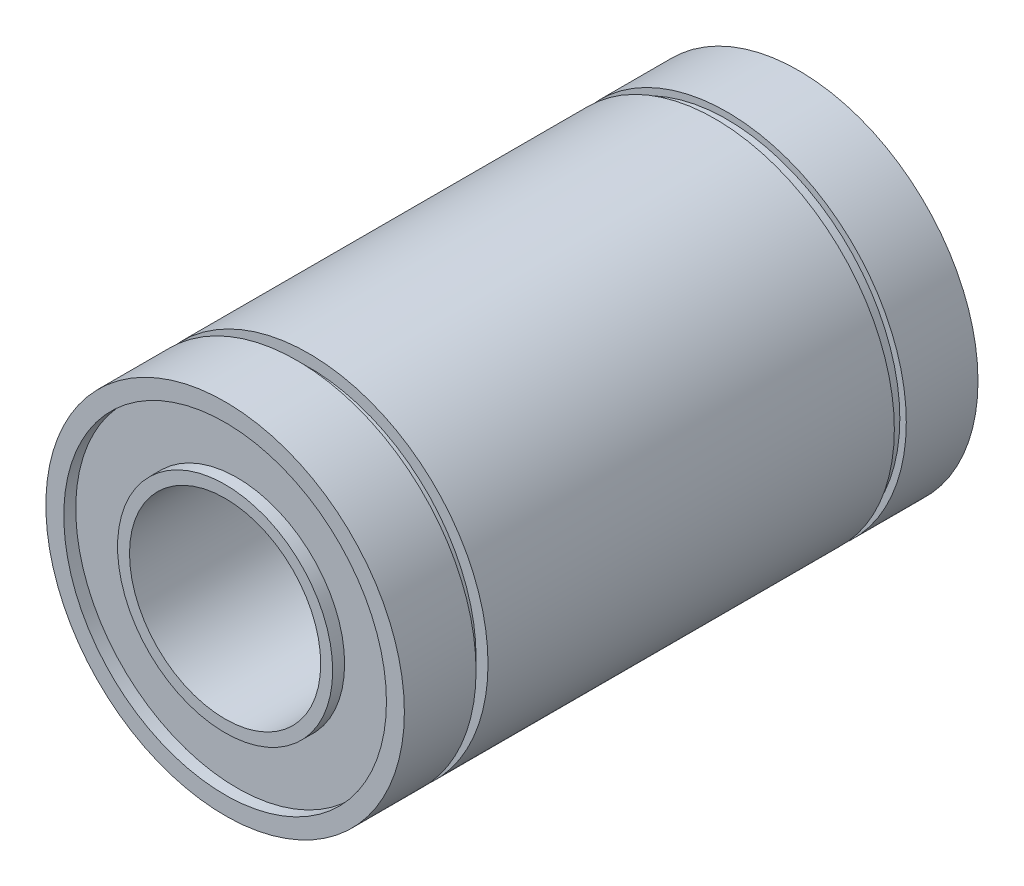
SolidWorks part; units mm, degrees
ref_plane "Front Plane" through (0, 0, 0) normal (0, 0, 1) x (1, 0, 0)
ref_plane "Top Plane" through (0, 0, 0) normal (0, 1, 0) x (1, 0, 0)
ref_plane "Right Plane" through (0, 0, 0) normal (1, 0, 0) x (0, 0, -1)
sketch "Sketch1" plane through (0, 0, 0) normal (0, 1, 0) x (1, 0, 0)
  line L0 (0, 0) -> (4.5, 0) construction
  line L1 (0, 0) -> (0, 126.2088) construction
  line L2 (4, 0) -> (4.5, 0)
  line L3 (7.5, 0) -> (7.5, 3)
  line L4 (7.5, 3) -> (7, 3)
  line L5 (7, 3) -> (7, 3.5)
  line L6 (7, 3.5) -> (7.5, 3.5)
  line L7 (7.5, 3.5) -> (7.5, 20.5)
  line L8 (7.5, 20.5) -> (7.2298, 20.5)
  line L9 (7.2298, 20.5) -> (7.2298, 21)
  line L10 (7.2298, 21) -> (7.5, 21)
  line L11 (7.5, 21) -> (7.5, 24)
  line L12 (7.5, 24) -> (6.75, 24)
  line L13 (4, 24) -> (4, 0)
  line L14 (6.75, 0) -> (6.75, 0.5)
  line L15 (6.75, 0.5) -> (4.5, 0.5)
  line L16 (4.5, 0.5) -> (4.5, 0)
  line L17 (6.75, 0) -> (7.5, 0)
  line L18 (6.75, 0) -> (93.3347, 0) construction
  line L19 (6.75, 24) -> (6.75, 23.5)
  line L20 (6.75, 23.5) -> (4.5, 23.5)
  line L21 (4.5, 23.5) -> (4.5, 24)
  line L22 (4.5, 24) -> (4, 24)
  point P22 (0, 0)
  point P25 (0, 0)
  dimension "D1" = 4
  dimension "D2" = 7.5
  dimension "D3" = 7.5
  dimension "D4" = 24
  dimension "D5" = 3
  dimension "D6" = 3
  dimension "D7" = 0.5
  dimension "D8" = 0.5
  dimension "D9" = 0.5
  dimension "D10" = 0.5
  dimension "D11" = 0.75
  dimension "D12" = 0.5
  dimension "D13" = 0.5
  dimension "D14" = 0.75
  dimension "D15" = 0.2702
revolve "Revolve1" add sketch "Sketch1" angle 360 about L1
